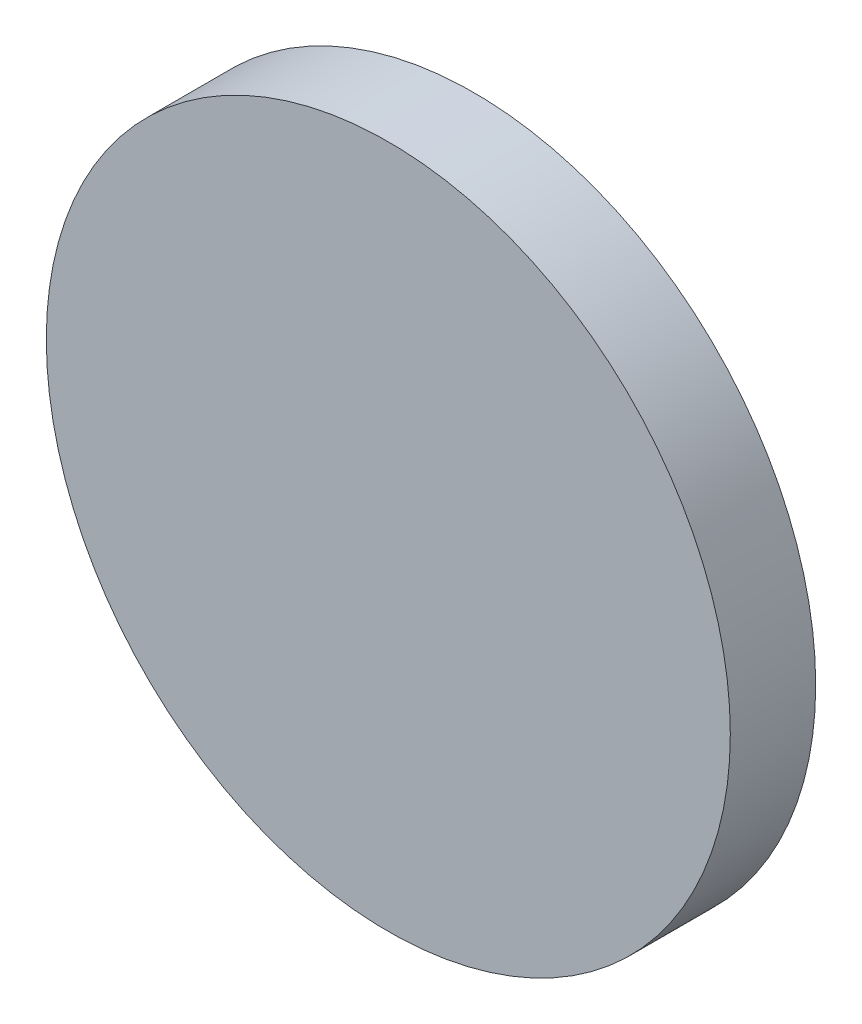
SolidWorks part; units mm, degrees
ref_plane "Спереди" through (0, 0, 0) normal (0, 0, 1) x (1, 0, 0)
ref_plane "Сверху" through (0, 0, 0) normal (0, 1, 0) x (1, 0, 0)
ref_plane "Справа" through (0, 0, 0) normal (1, 0, 0) x (0, 0, -1)
sketch "Эскиз1" plane through (0, 0, 0) normal (0, 0, 1) x (1, 0, 0)
  circle A0 centre (-8.1311, -7.0465) radius 200.288
extrude "Бобышка-Вытянуть1" add sketch "Эскиз1" along normal blind 50
